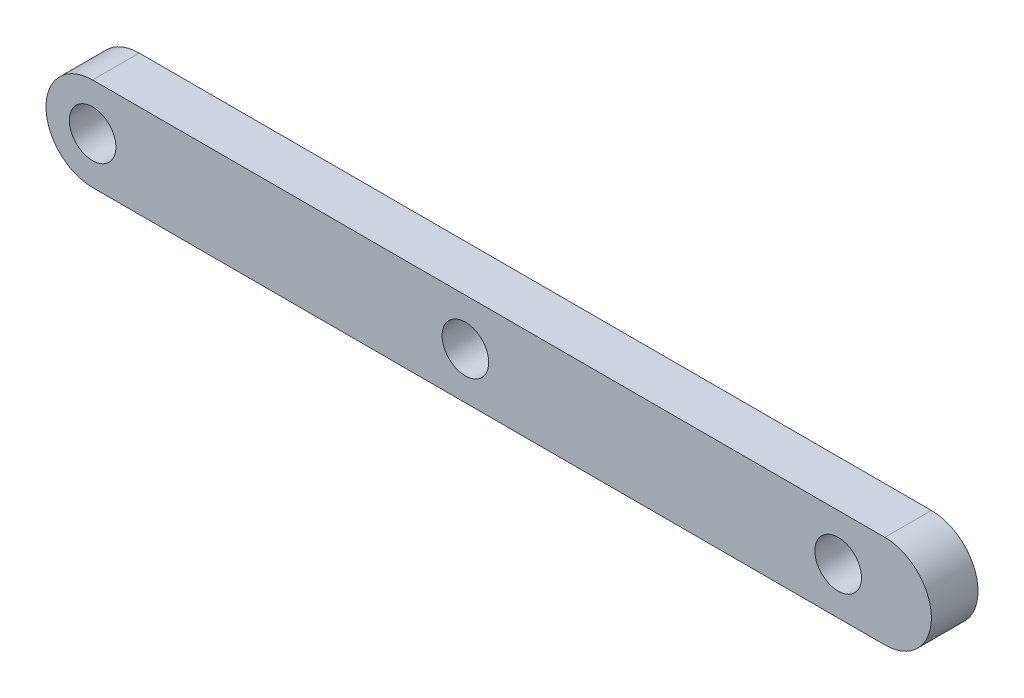
SolidWorks part; units mm, degrees
ref_plane "Alzado" through (0, 0, 0) normal (0, 0, 1) x (1, 0, 0)
ref_plane "Planta" through (0, 0, 0) normal (0, 1, 0) x (1, 0, 0)
ref_plane "Vista lateral" through (0, 0, 0) normal (1, 0, 0) x (0, 0, -1)
sketch "Croquis1" plane through (0, 0, 0) normal (0, 0, 1) x (1, 0, 0)
  line L0 (0, 0) -> (34, 0) construction
  line L1 (0, 2) -> (34, 2)
  line L2 (0, -2) -> (34, -2)
  arc A0 (0, 2) -> (0, -2) centre (0, 0) ccw
  arc A1 (34, -2) -> (34, 2) centre (34, 0) ccw
  point P3 (17, 0)
  point P8 (-2, 0)
  point P9 (36, 0)
  dimension "D1" = 4
  dimension "D2" = 38
extrude "Saliente-Extruir1" add sketch "Croquis1" along normal blind 2
sketch "Croquis2" plane through (0, 0, 2) normal (0, 0, 1) x (1, 0, 0)
  circle A0 centre (0, 0) radius 1
  circle A1 centre (16, 0) radius 1
  circle A2 centre (32, 0) radius 1
  dimension "D1" = 2
  dimension "D2" = 3
extrude "Cortar-Extruir1" cut sketch "Croquis2" against normal blind 2
